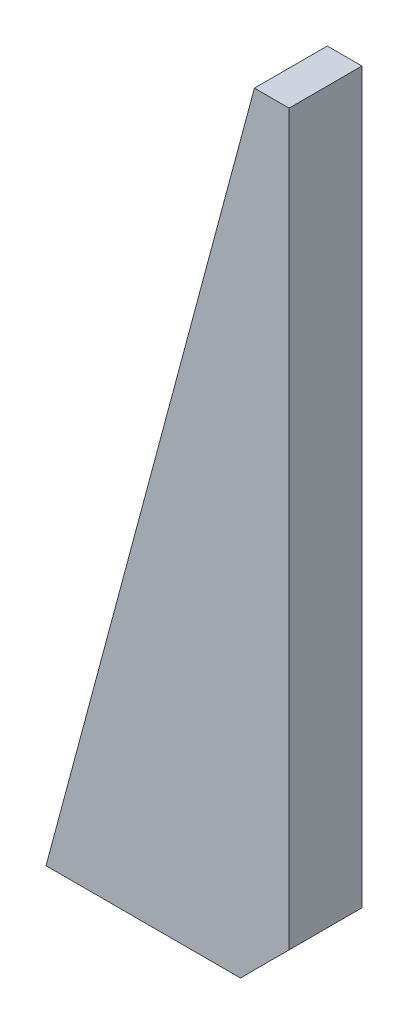
SolidWorks part; units mm, degrees
ref_plane "前基準面" through (0, 0, 0) normal (0, 0, 1) x (1, 0, 0)
ref_plane "上基準面" through (0, 0, 0) normal (0, 1, 0) x (1, 0, 0)
ref_plane "右基準面" through (0, 0, 0) normal (1, 0, 0) x (0, 0, -1)
ref_plane "平面1"
sketch "草圖1" plane through (0, 0, 0) normal (0, 0, 1) x (1, 0, 0)
  line L0 (0, 0) -> (-50, 0)
  line L1 (-50, 0) -> (-7.1281, 160)
  line L2 (-7.1281, 160) -> (0, 160)
  line L3 (0, 160) -> (0, 0)
  dimension "D1" = 50
  dimension "D2" = 160
extrude "擠出1" add sketch "草圖1" against normal blind 15
chamfer "倒角1" distance 10 distance2 10 1 edges at (0, 0, -7.5)
